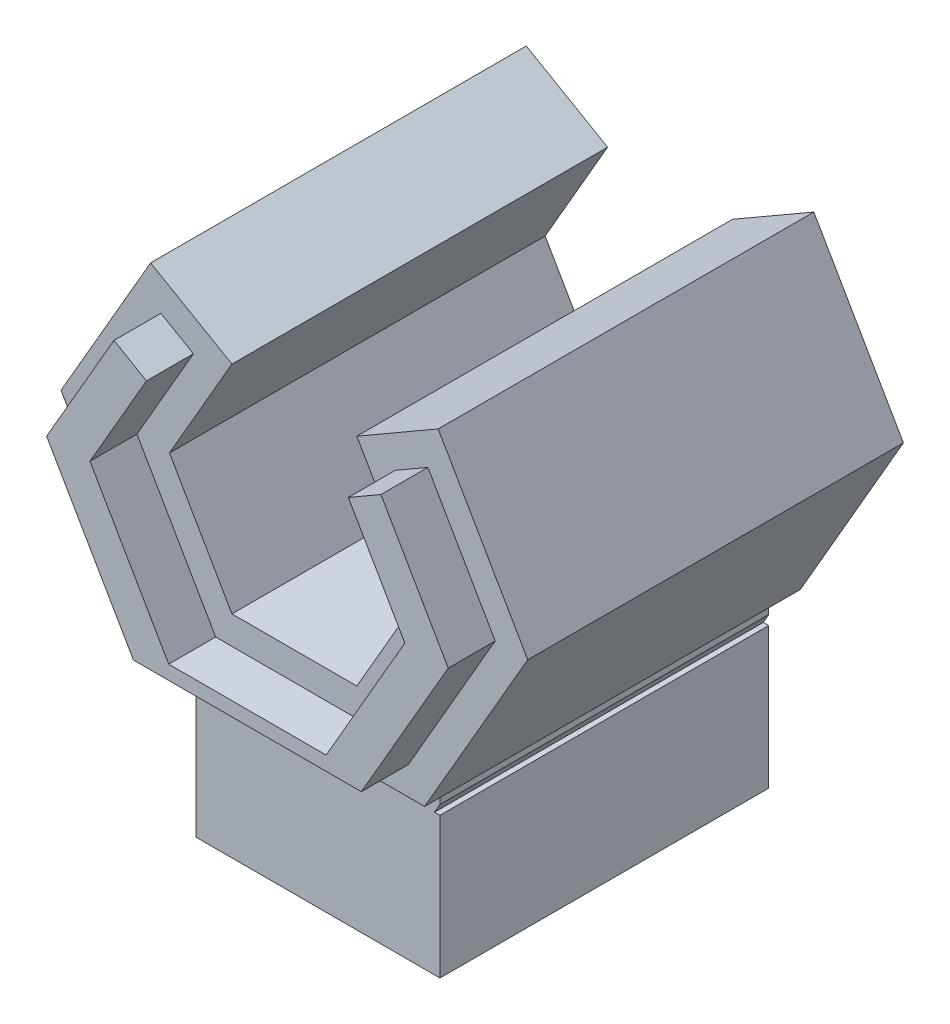
SolidWorks part; units mm, degrees
ref_plane "前视基准面" through (0, 0, 0) normal (0, 0, 1) x (1, 0, 0)
ref_plane "上视基准面" through (0, 0, 0) normal (0, 1, 0) x (1, 0, 0)
ref_plane "右视基准面" through (0, 0, 0) normal (1, 0, 0) x (0, 0, -1)
sketch "草图1" plane through (0, 0, 0) normal (0, 0, 1) x (1, 0, 0)
  line L0 (-2.66, 0) -> (-1.33, 2.3036) construction
  line L2 (1.33, 2.3036) -> (2.66, 0) construction
  line L3 (2.66, 0) -> (1.33, -2.3036) construction
  line L4 (1.33, -2.3036) -> (-1.33, -2.3036) construction
  line L5 (-1.33, -2.3036) -> (-2.66, 0) construction
  line L6 (-2.66, 0) -> (2.66, 0) construction
  line L13 (-3.0621, 3.3036) -> (-4.9694, 0)
  line L14 (-4.9694, 0) -> (-2.4847, -4.3036)
  line L15 (-2.4847, -4.3036) -> (2.4847, -4.3036)
  line L16 (2.4847, -4.3036) -> (4.9694, 0)
  line L19 (-1.33, 2.3036) -> (-2.66, 0)
  line L20 (-2.66, 0) -> (-1.33, -2.3036)
  line L21 (-1.33, -2.3036) -> (1.33, -2.3036)
  line L22 (1.33, -2.3036) -> (2.66, 0)
  line L23 (2.66, 0) -> (1.33, 2.3036)
  line L24 (4.9694, 0) -> (3.0621, 3.3036)
  line L25 (-3.0621, 3.3036) -> (-1.33, 2.3036)
  line L26 (1.33, 2.3036) -> (3.0621, 3.3036)
  point P2 (0, 0)
  dimension "D1" = 2.66
  dimension "D2" = 2
extrude "凸台-拉伸1" add sketch "草图1" along normal blind 8
sketch "草图2" plane through (0, -4.3036, 0) normal (0, -1, 0) x (1, 0, 0)
  line L0 (-4.9694, 8) -> (-2.4847, 8) construction
  line L1 (-4.5, 8) -> (4.5, 8)
  line L2 (-4.5, 8) -> (-4.5, 0)
  line L3 (-4.5, 0) -> (4.5, 0)
  line L4 (4.5, 8) -> (4.5, 0)
  line L5 (2.4847, 0) -> (4.9694, 0) construction
  dimension "D1" = 9
  dimension "D2" = 4.5
extrude "凸台-拉伸2" add sketch "草图2" along normal blind 3
sketch "草图3" plane through (0, -7.3036, 0) normal (0, -1, 0) x (1, 0, 0)
  line L0 (-4.5, 8) -> (4.5, 0) construction
  line L1 (4.5, 8) -> (-4.5, 0) construction
  line L3 (-1, 6.5) -> (1, 6.5)
  line L12 (-1, 6.5) -> (-1, 1.5)
  line L13 (-1, 1.5) -> (1, 1.5)
  line L14 (1, 6.5) -> (1, 1.5)
  line L15 (-1, 6.5) -> (1, 1.5) construction
  line L16 (-1, 1.5) -> (1, 6.5) construction
  line L17 (-2.6, 7.5) -> (2.6, 7.5)
  line L18 (-2.6, 7.5) -> (-2.6, 0.5)
  line L19 (-2.6, 0.5) -> (2.6, 0.5)
  line L20 (2.6, 7.5) -> (2.6, 0.5)
  line L21 (-2.6, 7.5) -> (2.6, 0.5) construction
  line L22 (-2.6, 0.5) -> (2.6, 7.5) construction
  point P2 (0, 4)
  point P4 (0, 4)
  point P11 (0, 4)
  dimension "D2" = 5
  dimension "D3" = 2
  dimension "D4" = 5.2
  dimension "D5" = 7
extrude "切除-拉伸1" cut sketch "草图3" against normal blind 3.5 flip side to cut
sketch "草图4" plane through (0, 0, 8) normal (0, 0, 1) x (1, 0, 0)
  line L0 (-4.2766, 0) -> (-2.427, -3.2036)
  line L1 (-2.427, -3.2036) -> (2.427, -3.2036)
  line L2 (2.427, -3.2036) -> (4.2766, 0)
  line L3 (4.2766, 0) -> (2.8424, 2.484)
  line L4 (2.8424, 2.484) -> (2.1496, 2.084)
  line L5 (2.1496, 2.084) -> (3.3528, 0)
  line L6 (3.3528, 0) -> (1.6764, -2.9036)
  line L7 (1.6764, -2.9036) -> (-1.6764, -2.9036)
  line L8 (-1.6764, -2.9036) -> (-3.3528, 0)
  line L9 (-3.3528, 0) -> (-2.1496, 2.084)
  line L10 (-2.1496, 2.084) -> (-2.8424, 2.484)
  line L11 (-2.8424, 2.484) -> (-4.2766, 0)
extrude "凸台-拉伸3" add sketch "草图4" along normal blind 1
